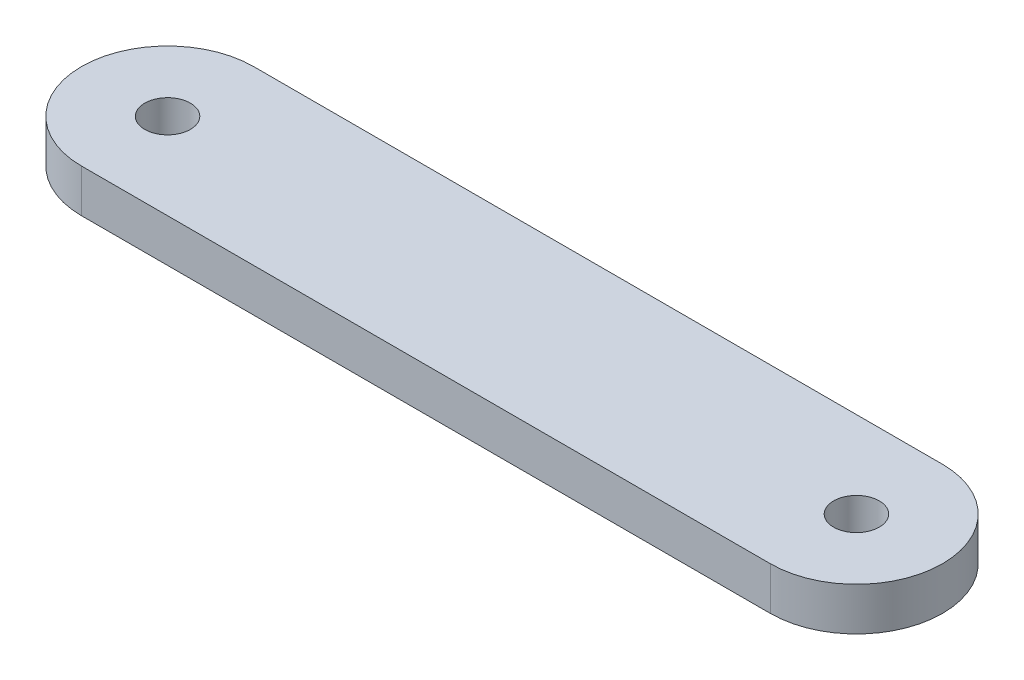
SolidWorks part; units mm, degrees
ref_plane "Alzado" through (0, 0, 0) normal (0, 0, 1) x (1, 0, 0)
ref_plane "Planta" through (0, 0, 0) normal (0, 1, 0) x (1, 0, 0)
ref_plane "Vista lateral" through (0, 0, 0) normal (1, 0, 0) x (0, 0, -1)
sketch "Croquis1" plane through (0, 0, 0) normal (0, 1, 0) x (1, 0, 0)
  line L0 (0, 0) -> (-80, 0) construction
  line L1 (0, -10) -> (-80, -10)
  line L2 (0, 10) -> (-80, 10)
  arc A0 (0, -10) -> (0, 10) centre (0, 0) ccw
  arc A1 (-80, 10) -> (-80, -10) centre (-80, 0) ccw
  circle A2 centre (-80, 0) radius 2.65
  circle A3 centre (0, 0) radius 2.65
  point P3 (-40, 0)
  dimension "D2" = 10
  dimension "D3" = 5.3
  dimension "D4" = 5.3
  dimension "D1" = 80
extrude "Saliente-Extruir1" add sketch "Croquis1" along normal blind 5
